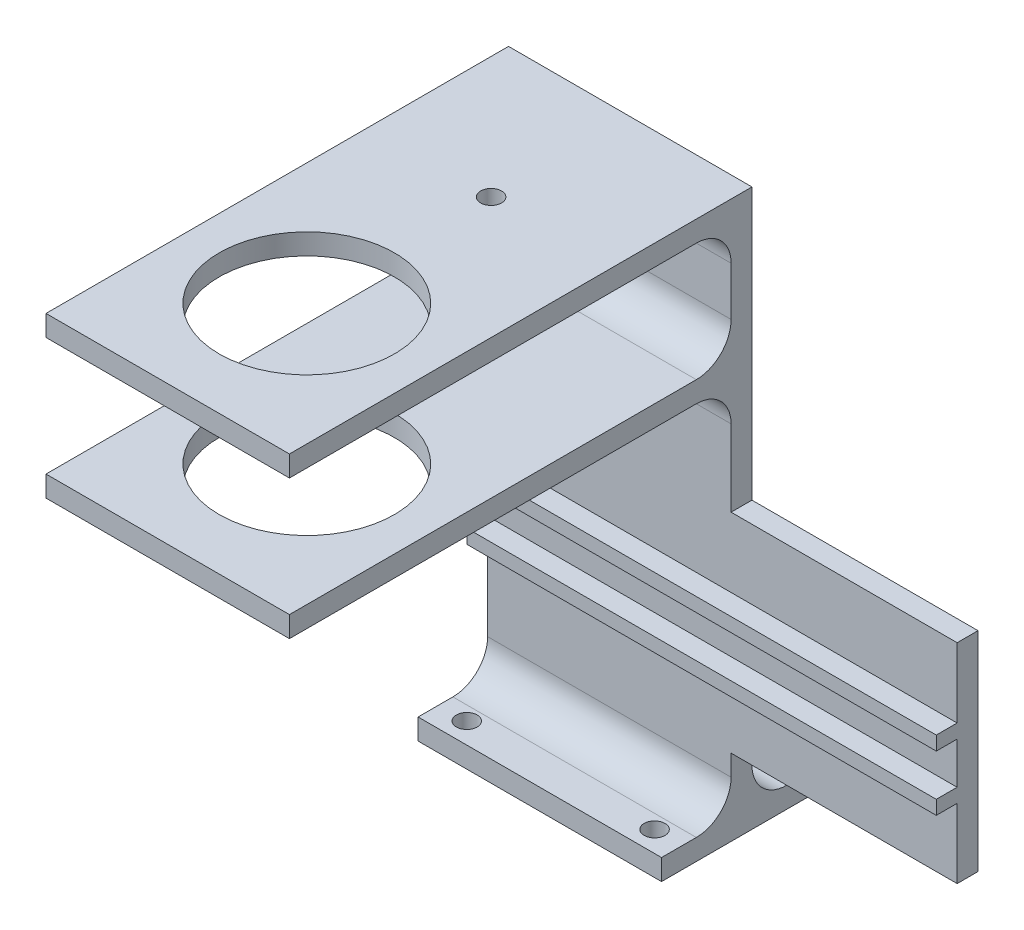
SolidWorks part; units mm, degrees
ref_plane "Front Plane" through (0, 0, 0) normal (0, 0, 1) x (1, 0, 0)
ref_plane "Top Plane" through (0, 0, 0) normal (0, 1, 0) x (1, 0, 0)
ref_plane "Right Plane" through (0, 0, 0) normal (1, 0, 0) x (0, 0, -1)
sketch "Sketch1" plane through (0, 0, 0) normal (0, 1, 0) x (1, 0, 0)
  line L1 (-17.5, 20) -> (17.5, 20)
  line L2 (-17.5, 20) -> (-17.5, -20)
  line L3 (-17.5, -20) -> (17.5, -20)
  line L4 (17.5, 20) -> (17.5, -20)
  line L5 (-17.5, 20) -> (17.5, -20) construction
  line L6 (-17.5, -20) -> (17.5, 20) construction
  point P0 (0, 0)
  dimension "D1" = 40
  dimension "D2" = 35
extrude "Boss-Extrude1" add sketch "Sketch1" along normal blind 3
sketch "Sketch2" plane through (0, 3, 0) normal (0, 1, 0) x (1, 0, 0)
  circle A0 centre (0, 0) radius 12.6
  dimension "D1" = 25.2
extrude "Cut-Extrude1" cut sketch "Sketch2" against normal through all
ref_plane "Plane1" through (17.5, 0, -20) normal (-1, 0, 0) x (0, 0, 1)
sketch "Sketch4" plane through (0, 0, -20) normal (0, 0, -1) x (-1, 0, 0)
  line L4 (-17.5, 0) -> (17.5, 0)
  line L5 (17.5, 0) -> (17.5, 3)
  line L6 (17.5, 3) -> (-17.5, 3)
  line L7 (-17.5, 3) -> (-17.5, 0)
  line L8 (-17.5, 0) -> (17.5, 0)
  line L9 (17.5, 0) -> (17.5, 3)
  line L10 (17.5, 3) -> (-17.5, 3)
  line L11 (-17.5, 3) -> (-17.5, 0)
  dimension "D1" = 0
extrude "Boss-Extrude2" add sketch "Sketch4" along normal blind 23.5
sketch "Sketch5" plane through (0, 0, -43.5) normal (0, 0, -1) x (-1, 0, 0)
  line L0 (17.5, 0) -> (17.5, 3) construction
  line L1 (-17.5, 3) -> (17.5, 3)
  line L2 (-17.5, 3) -> (-17.5, -77)
  line L3 (-17.5, -77) -> (17.5, -77)
  line L4 (17.5, 3) -> (17.5, -77)
  dimension "D1" = 80
extrude "Boss-Extrude3" add sketch "Sketch5" along normal blind 3
ref_plane "Plane2" through (0, -17, 0) normal (0, 1, 0) x (1, 0, 0)
sketch "Sketch6" plane through (0, -17, 0) normal (0, 1, 0) x (1, 0, 0)
  line L4 (17.5, -20) -> (17.5, 43.5)
  line L5 (-17.5, -20) -> (17.5, -20)
  line L6 (-17.5, 43.5) -> (-17.5, -20)
  line L7 (17.5, 43.5) -> (-17.5, 43.5)
  line L8 (17.5, -20) -> (17.5, 43.5)
  line L9 (-17.5, -20) -> (17.5, -20)
  line L10 (-17.5, 43.5) -> (-17.5, -20)
  line L11 (17.5, 43.5) -> (-17.5, 43.5)
  circle A0 centre (0, 0) radius 12.6 construction
  circle A1 centre (0, 0) radius 12.6
  dimension "D1" = 0
extrude "Boss-Extrude4" add sketch "Sketch6" against normal blind 3
sketch "Sketch7" plane through (0, 0, -43.5) normal (0, 0, 1) x (1, 0, 0)
  line L0 (-17.5, -77) -> (-17.5, -20) construction
  line L1 (-17.5, -74) -> (17.5, -74)
  line L2 (-17.5, -74) -> (-17.5, -77)
  line L3 (-17.5, -77) -> (17.5, -77)
  line L4 (17.5, -74) -> (17.5, -77)
  dimension "D1" = 3
extrude "Boss-Extrude5" add sketch "Sketch7" along normal blind 10 and the other way blind 13
fillet "Fillet1" radius 5 5 edges at (0, -20, -43.5) (0, -17, -43.5) (0, 0, -43.5) (0, -74, -46.5) (0, -74, -43.5)
ref_plane "Plane3" through (0, 0, 0) normal (-1, 0, 0) x (0, 0, 1)
sketch "Sketch8" plane through (0, 0, -43.5) normal (0, 0, 1) x (1, 0, 0)
  line L0 (0, 42.075) -> (0, -42.075) construction
  line L1 (-50, -36) -> (50, -36)
  line L2 (-50, -36) -> (-50, -66)
  line L3 (-50, -66) -> (50, -66)
  line L4 (50, -36) -> (50, -66)
  line L5 (17.5, -69) -> (-17.5, -69) construction
  point P6 (0, -36)
  dimension "D1" = 100
  dimension "D2" = 30
  dimension "D3" = 3
extrude "Boss-Extrude6" add sketch "Sketch8" against normal up to surface (3 mm away) up to face at (0, -33, -46.5)
fillet "Fillet2" [suppressed] radius 5
sketch "Sketch10" plane through (0, 0, -43.5) normal (0, 0, 1) x (1, 0, 0)
  line L0 (-50, -36) -> (-50, -66) construction
  line L1 (-50, -46) -> (50, -46)
  line L2 (-50, -46) -> (-50, -48)
  line L3 (-50, -48) -> (50, -48)
  line L4 (50, -46) -> (50, -48)
  line L5 (50, -66) -> (50, -36) construction
  line L6 (-17.5, -77) -> (17.5, -77) construction
  line L7 (-50, -54) -> (50, -54)
  line L8 (-50, -54) -> (-50, -56)
  line L9 (-50, -56) -> (50, -56)
  line L10 (50, -54) -> (50, -56)
  dimension "D1" = 2
  dimension "D2" = 2
  dimension "D3" = 6
  dimension "D4" = 21
extrude "Boss-Extrude8" add sketch "Sketch10" along normal blind 3
sketch "Sketch11" plane through (50, 0, 0) normal (1, 0, 0) x (0, 0, -1)
  line L10 (43.5, -66) -> (46.5, -66)
  line L11 (46.5, -66) -> (46.5, -36)
  line L12 (46.5, -36) -> (43.5, -36)
  line L13 (43.5, -36) -> (43.5, -46)
  line L14 (43.5, -46) -> (40.5, -46)
  line L15 (40.5, -46) -> (40.5, -48)
  line L16 (40.5, -48) -> (43.5, -48)
  line L17 (43.5, -48) -> (43.5, -54)
  line L18 (43.5, -54) -> (40.5, -54)
  line L19 (40.5, -54) -> (40.5, -56)
  line L20 (43.5, -66) -> (46.5, -66)
  line L21 (46.5, -66) -> (46.5, -36)
  line L22 (46.5, -36) -> (43.5, -36)
  line L23 (43.5, -36) -> (43.5, -46)
  line L24 (43.5, -46) -> (40.5, -46)
  line L25 (40.5, -46) -> (40.5, -48)
  line L26 (40.5, -48) -> (43.5, -48)
  line L27 (43.5, -48) -> (43.5, -54)
  line L28 (43.5, -54) -> (40.5, -54)
  line L29 (40.5, -54) -> (40.5, -56)
  line L32 (40.5, -56) -> (43.5, -56)
  line L33 (40.5, -56) -> (43.5, -56)
  line L34 (43.5, -56) -> (43.5, -66)
  line L35 (43.5, -56) -> (43.5, -66)
  dimension "D1" = 0
extrude "Cut-Extrude2" [suppressed] cut sketch "Sketch11" against normal up to surface (32.5 mm away)
sketch "Sketch12" plane through (0, -74, 0) normal (0, 1, 0) x (1, 0, 0)
  line L0 (-17.5, 38.5) -> (-17.5, 33.5) construction
  line L1 (17.5, 33.5) -> (-17.5, 33.5) construction
  circle A0 centre (-13.5, 36.5) radius 1.5
  dimension "D1" = 3
  dimension "D2" = 4
  dimension "D3" = 3
extrude "Cut-Extrude3" cut sketch "Sketch12" against normal through all
ref_plane "Plane4" through (0, 0, -45) normal (0, 0, -1) x (-1, 0, 0)
mirror "Mirror1" about plane through (0, 0, 0) normal (-1, 0, 0) of "Cut-Extrude3"
mirror "Mirror2" about plane through (0, 0, -45) normal (0, 0, -1) of "Mirror1", "Cut-Extrude3"
sketch "Sketch13" plane through (-50, 0, 0) normal (-1, 0, 0) x (0, 0, 1)
  line L12 (-43.5, -36) -> (-46.5, -36)
  line L13 (-46.5, -36) -> (-46.5, -66)
  line L14 (-46.5, -66) -> (-43.5, -66)
  line L15 (-43.5, -66) -> (-43.5, -56)
  line L16 (-43.5, -56) -> (-40.5, -56)
  line L17 (-40.5, -56) -> (-40.5, -54)
  line L18 (-40.5, -54) -> (-43.5, -54)
  line L19 (-43.5, -54) -> (-43.5, -48)
  line L20 (-43.5, -48) -> (-40.5, -48)
  line L21 (-40.5, -48) -> (-40.5, -46)
  line L22 (-40.5, -46) -> (-43.5, -46)
  line L23 (-43.5, -46) -> (-43.5, -36)
  line L24 (-43.5, -36) -> (-46.5, -36)
  line L25 (-46.5, -36) -> (-46.5, -66)
  line L26 (-46.5, -66) -> (-43.5, -66)
  line L27 (-43.5, -66) -> (-43.5, -56)
  line L28 (-43.5, -56) -> (-40.5, -56)
  line L29 (-40.5, -56) -> (-40.5, -54)
  line L30 (-40.5, -54) -> (-43.5, -54)
  line L31 (-43.5, -54) -> (-43.5, -48)
  line L32 (-43.5, -48) -> (-40.5, -48)
  line L33 (-40.5, -48) -> (-40.5, -46)
  line L34 (-40.5, -46) -> (-43.5, -46)
  line L35 (-43.5, -46) -> (-43.5, -36)
  dimension "D1" = 0
extrude "Cut-Extrude4" cut sketch "Sketch13" against normal up to surface (32.5 mm away) up to face at (-17.5, -13.9203, -23.5082)
sketch "Sketch26" plane through (0, 3, 0) normal (0, 1, 0) x (1, 0, 0)
  line L0 (-17.5, 46.5) -> (17.5, 46.5) construction
  circle A0 centre (0, 26.5) radius 1.5
  dimension "D1" = 3
  dimension "D2" = 20
extrude "Cut-Extrude17" cut sketch "Sketch26" against normal blind 10
